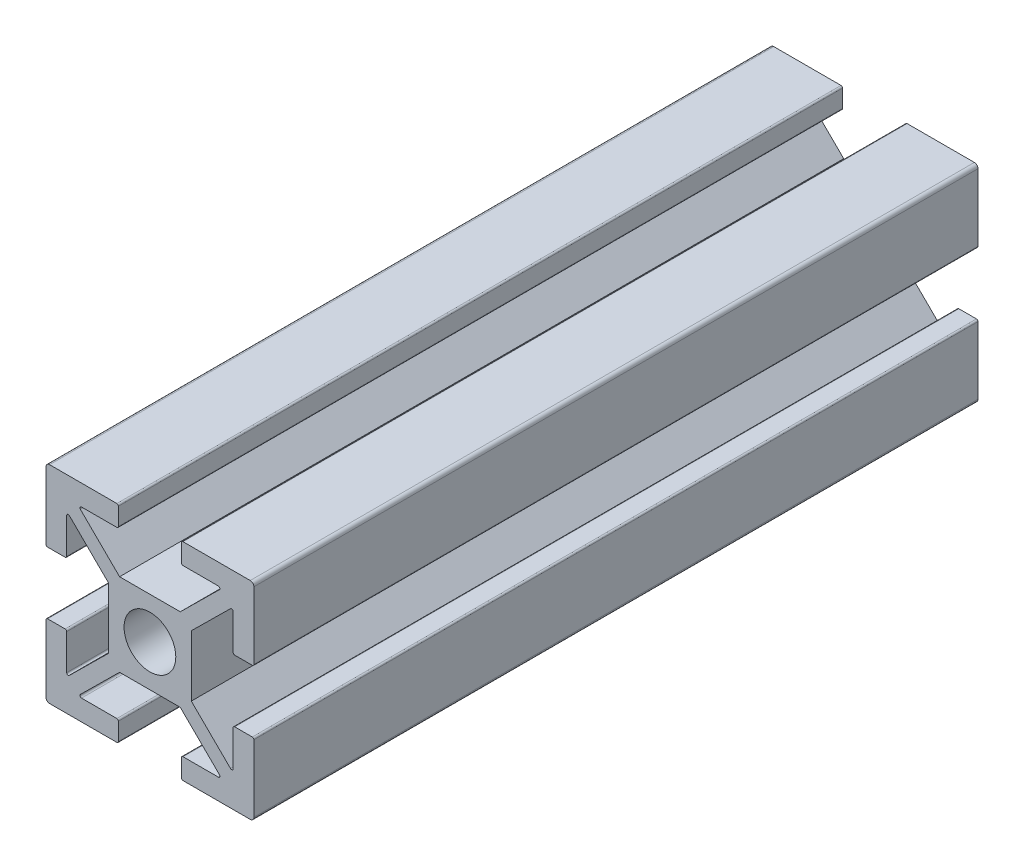
SolidWorks part; units mm, degrees
ref_plane "Front Plane" through (0, 0, 0) normal (0, 0, 1) x (1, 0, 0)
ref_plane "Top Plane" through (0, 0, 0) normal (0, 1, 0) x (1, 0, 0)
ref_plane "Right Plane" through (0, 0, 0) normal (1, 0, 0) x (0, 0, -1)
sketch "Sketch1" plane through (0, 0, 0) normal (0, 0, 1) x (1, 0, 0)
  line L0 (-31.3764, -0.0618) -> (-29.6764, -0.0618)
  line L1 (-24.6764, 6.9382) -> (-31.1764, 6.9382)
  line L2 (-31.5264, 0.0882) -> (-31.5264, 6.5882)
  line L3 (-18.5469, 0.9382) -> (-24.4133, 0.9382)
  line L4 (-25.4801, -6.0072) -> (-25.4801, -0.1164)
  line L5 (-29.5264, 0.0882) -> (-29.5264, 3.5244)
  line L6 (-28.0945, 4.9382) -> (-24.6764, 4.9382)
  line L7 (-24.5264, 5.0882) -> (-24.5264, 6.7882)
  line L8 (-29.5264, 4.9382) -> (-25.4801, 0.9382) construction
  line L9 (-29.271, 3.631) -> (-25.4801, -0.1164)
  line L10 (-28.1999, 4.6815) -> (-24.4133, 0.9382)
  line L11 (-13.4338, 4.9382) -> (-17.4801, 0.9382) construction
  line L12 (-21.4801, -3.0618) -> (-21.4801, 8.6268) construction
  line L13 (-21.4801, -3.0618) -> (-36.4642, -3.0618) construction
  line L14 (-14.7603, 4.6815) -> (-18.5469, 0.9382)
  line L15 (-13.6893, 3.631) -> (-17.4801, -0.1164)
  line L16 (-18.4338, 5.0882) -> (-18.4338, 6.7882)
  line L17 (-14.8657, 4.9382) -> (-18.2838, 4.9382)
  line L18 (-13.4338, 0.0882) -> (-13.4338, 3.5244)
  line L19 (-17.4801, -6.0072) -> (-17.4801, -0.1164)
  line L20 (-11.4338, 0.0882) -> (-11.4338, 6.5882)
  line L21 (-18.2838, 6.9382) -> (-11.7838, 6.9382)
  line L22 (-11.5838, -0.0618) -> (-13.2838, -0.0618)
  line L23 (-13.4338, -11.0618) -> (-17.4801, -7.0618) construction
  line L24 (-29.5264, -11.0618) -> (-25.4801, -7.0618) construction
  line L25 (-11.5838, -6.0618) -> (-13.2838, -6.0618)
  line L26 (-18.2838, -13.0618) -> (-11.7838, -13.0618)
  line L27 (-11.4338, -6.2118) -> (-11.4338, -12.7118)
  line L28 (-13.4338, -6.2118) -> (-13.4338, -9.648)
  line L29 (-14.8657, -11.0618) -> (-18.2838, -11.0618)
  line L30 (-18.4338, -11.2118) -> (-18.4338, -12.9118)
  line L31 (-13.6893, -9.7547) -> (-17.4801, -6.0072)
  line L32 (-14.7603, -10.8051) -> (-18.5469, -7.0618)
  line L33 (-28.1999, -10.8051) -> (-24.4133, -7.0618)
  line L34 (-29.271, -9.7547) -> (-25.4801, -6.0072)
  line L35 (-24.5264, -11.2118) -> (-24.5264, -12.9118)
  line L36 (-28.0945, -11.0618) -> (-24.6764, -11.0618)
  line L37 (-29.5264, -6.2118) -> (-29.5264, -9.648)
  line L38 (-18.5469, -7.0618) -> (-24.4133, -7.0618)
  line L39 (-31.5264, -6.2118) -> (-31.5264, -12.7118)
  line L40 (-24.6764, -13.0618) -> (-31.1764, -13.0618)
  line L41 (-31.3764, -6.0618) -> (-29.6764, -6.0618)
  circle A0 centre (-21.4801, -3.0618) radius 2.5
  arc A1 (-31.5264, 6.5882) -> (-31.1764, 6.9382) centre (-31.1764, 6.5882) cw
  arc A2 (-31.3764, -0.0618) -> (-31.5264, 0.0882) centre (-31.3764, 0.0882) cw
  arc A3 (-29.6764, -0.0618) -> (-29.5264, 0.0882) centre (-29.6764, 0.0882) ccw
  arc A4 (-24.6764, 6.9382) -> (-24.5264, 6.7882) centre (-24.6764, 6.7882) cw
  arc A5 (-24.6764, 4.9382) -> (-24.5264, 5.0882) centre (-24.6764, 5.0882) ccw
  arc A6 (-28.1999, 4.6815) -> (-28.0945, 4.9382) centre (-28.0945, 4.7882) cw
  arc A7 (-29.271, 3.631) -> (-29.5264, 3.5244) centre (-29.3764, 3.5244) ccw
  arc A8 (-13.6893, 3.631) -> (-13.4338, 3.5244) centre (-13.5838, 3.5244) cw
  arc A9 (-14.7603, 4.6815) -> (-14.8657, 4.9382) centre (-14.8657, 4.7882) ccw
  arc A10 (-18.2838, 4.9382) -> (-18.4338, 5.0882) centre (-18.2838, 5.0882) cw
  arc A11 (-18.2838, 6.9382) -> (-18.4338, 6.7882) centre (-18.2838, 6.7882) ccw
  arc A12 (-13.2838, -0.0618) -> (-13.4338, 0.0882) centre (-13.2838, 0.0882) cw
  arc A13 (-11.5838, -0.0618) -> (-11.4338, 0.0882) centre (-11.5838, 0.0882) ccw
  arc A14 (-11.4338, 6.5882) -> (-11.7838, 6.9382) centre (-11.7838, 6.5882) ccw
  arc A15 (-11.4338, -12.7118) -> (-11.7838, -13.0618) centre (-11.7838, -12.7118) cw
  arc A16 (-11.5838, -6.0618) -> (-11.4338, -6.2118) centre (-11.5838, -6.2118) cw
  arc A17 (-13.2838, -6.0618) -> (-13.4338, -6.2118) centre (-13.2838, -6.2118) ccw
  arc A18 (-18.2838, -13.0618) -> (-18.4338, -12.9118) centre (-18.2838, -12.9118) cw
  arc A19 (-18.2838, -11.0618) -> (-18.4338, -11.2118) centre (-18.2838, -11.2118) ccw
  arc A20 (-14.7603, -10.8051) -> (-14.8657, -11.0618) centre (-14.8657, -10.9118) cw
  arc A21 (-13.6893, -9.7547) -> (-13.4338, -9.648) centre (-13.5838, -9.648) ccw
  arc A22 (-29.271, -9.7547) -> (-29.5264, -9.648) centre (-29.3764, -9.648) cw
  arc A23 (-28.1999, -10.8051) -> (-28.0945, -11.0618) centre (-28.0945, -10.9118) ccw
  arc A24 (-24.6764, -11.0618) -> (-24.5264, -11.2118) centre (-24.6764, -11.2118) cw
  arc A25 (-24.6764, -13.0618) -> (-24.5264, -12.9118) centre (-24.6764, -12.9118) ccw
  arc A26 (-29.6764, -6.0618) -> (-29.5264, -6.2118) centre (-29.6764, -6.2118) cw
  arc A27 (-31.3764, -6.0618) -> (-31.5264, -6.2118) centre (-31.3764, -6.2118) ccw
  arc A28 (-31.5264, -12.7118) -> (-31.1764, -13.0618) centre (-31.1764, -12.7118) ccw
  point P27 (-18.4338, 4.9382)
  point P28 (-11.4338, -13.0618)
  point P47 (-17.4801, -3.0618)
  point P57 (-21.4801, 0.9382)
  point P59 (-18.4338, 6.9382)
  point P60 (-13.4338, -0.0618)
  point P61 (-11.4338, -0.0618)
  point P62 (-11.4338, 6.9382)
  point P112 (-25.4801, -3.0618)
  point P113 (-11.4338, -6.0618)
  point P114 (-13.4338, -6.0618)
  point P115 (-18.4338, -13.0618)
  point P116 (-21.4801, -7.0618)
  point P117 (-24.5264, -11.0618)
  point P118 (-24.5264, -13.0618)
  point P119 (-29.5264, -6.0618)
  point P120 (-18.4338, -11.0618)
  point P121 (-31.5264, -6.0618)
  point P122 (-31.5264, -13.0618)
  dimension "D3" = 0.35
  dimension "D4" = 0.15
  dimension "D5" = 0.15
  dimension "D6" = 0.15
  dimension "D7" = 0.15
  dimension "D8" = 0.15
  dimension "D9" = 0.15
  dimension "D1" = 0.75
  dimension "D2" = 0.75
extrude "Boss-Extrude1" add sketch "Sketch1" along normal blind 70
